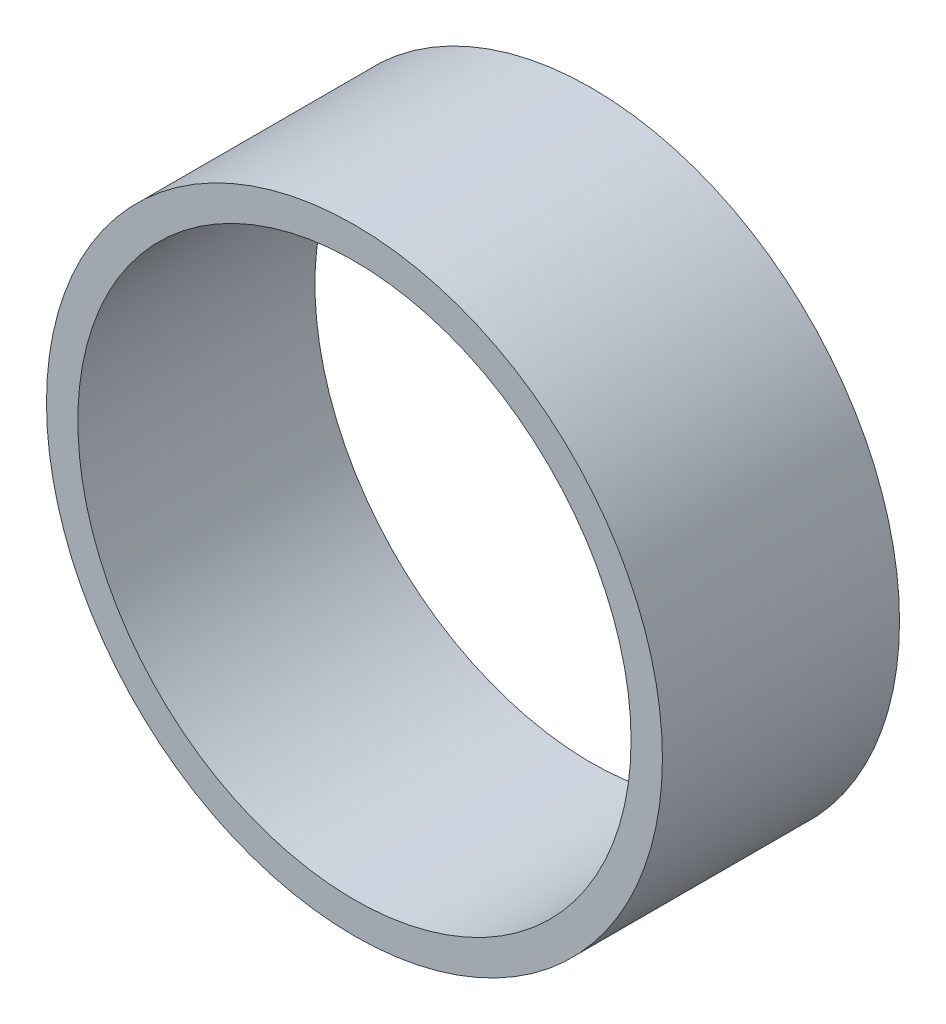
SolidWorks part; units mm, degrees
material "Rubber"
ref_plane "Front Plane" through (0, 0, 0) normal (0, 0, 1) x (1, 0, 0)
ref_plane "Top Plane" through (0, 0, 0) normal (0, 1, 0) x (1, 0, 0)
ref_plane "Right Plane" through (0, 0, 0) normal (1, 0, 0) x (0, 0, -1)
sketch "Sketch2" plane through (0, 0, 0) normal (0, 0, 1) x (1, 0, 0)
  circle A0 centre (0, 0) radius 13.335
  circle A1 centre (0, 0) radius 14.8463
  dimension "D1" = 26.67
  dimension "D2" = 29.6926
extrude "Boss-Extrude1" add sketch "Sketch2" along normal blind 11.43
